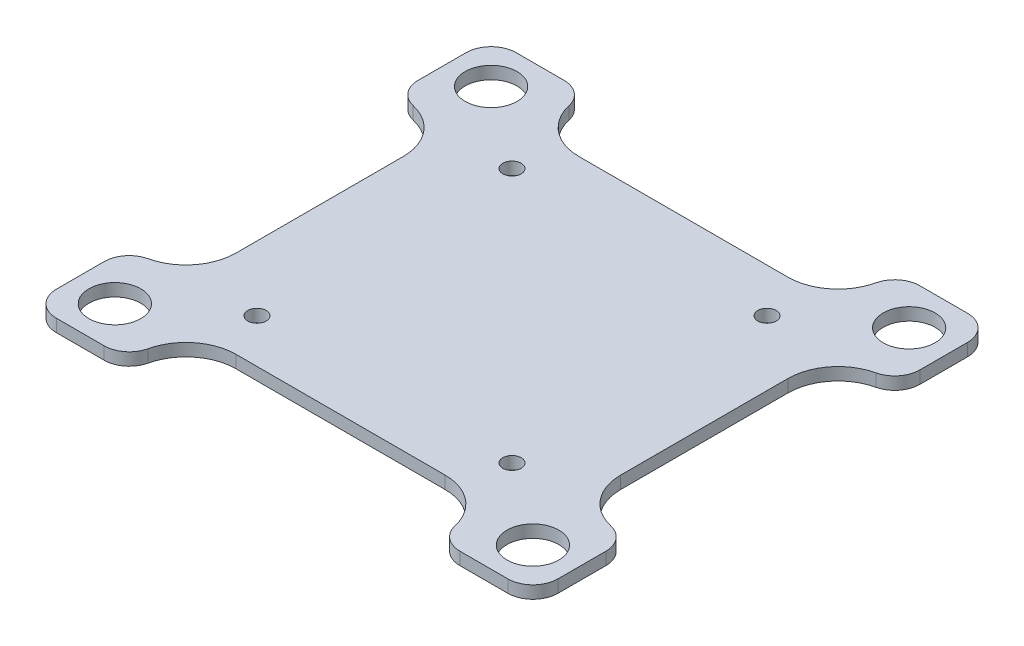
SolidWorks part; units mm, degrees
ref_plane "Front Plane" through (0, 0, 0) normal (0, 0, 1) x (1, 0, 0)
ref_plane "Top Plane" through (0, 0, 0) normal (0, 1, 0) x (1, 0, 0)
ref_plane "Right Plane" through (0, 0, 0) normal (1, 0, 0) x (0, 0, -1)
sketch "Sketch1" plane through (0, 0, 0) normal (0, 1, 0) x (1, 0, 0)
  line L1 (30, 27.5) -> (-30, 27.5)
  line L2 (30, 27.5) -> (30, -27.5)
  line L3 (30, -27.5) -> (-30, -27.5)
  line L4 (-30, 27.5) -> (-30, -27.5)
  line L5 (30, 27.5) -> (-30, -27.5) construction
  line L6 (30, -27.5) -> (-30, 27.5) construction
  point P0 (0, 0)
  dimension "D1" = 60
  dimension "D2" = 55
extrude "Boss-Extrude1" add sketch "Sketch1" along normal blind 1.5
sketch "Sketch2" plane through (0, 1.5, 0) normal (0, 1, 0) x (1, 0, 0)
  line L0 (0, 0) -> (0, -50000) construction
  line L1 (0, 0) -> (-50000, 0) construction
  circle A0 centre (-25, 22.5) radius 3.1
  circle A1 centre (25, 22.5) radius 3.1
  circle A2 centre (-25, -22.5) radius 3.1
  circle A3 centre (25, -22.5) radius 3.1
  dimension "D2" = 6.2
  dimension "D1" = 50
  dimension "D3" = 45
extrude "Cut-Extrude1" cut sketch "Sketch2" against normal through all
fillet "Fillet1" radius 3 4 edges at (30, 0.75, 27.5) (-30, 0.75, 27.5) (30, 0.75, -27.5) (-30, 0.75, -27.5)
sketch "Sketch4" plane through (0, 1.5, 0) normal (0, 1, 0) x (1, 0, 0)
  line L0 (27, 27.5) -> (-27, 27.5) construction
  line L1 (-18.5, 27.5) -> (18.5, 27.5)
  line L2 (-18.5, 27.5) -> (-18.5, 20.5)
  line L3 (-18.5, 20.5) -> (18.5, 20.5)
  line L4 (18.5, 27.5) -> (18.5, 20.5)
  line L5 (0, 0) -> (0, -50000) construction
  line L6 (0, 0) -> (-50000, 0) construction
  line L7 (-30, 24.5) -> (-30, -24.5) construction
  line L8 (-30, 16) -> (-23, 16)
  line L9 (-30, 16) -> (-30, -16)
  line L10 (-30, -16) -> (-23, -16)
  line L11 (-23, 16) -> (-23, -16)
  line L12 (18.5, -27.5) -> (18.5, -20.5)
  line L13 (-18.5, -20.5) -> (18.5, -20.5)
  line L14 (-18.5, -27.5) -> (-18.5, -20.5)
  line L15 (-18.5, -27.5) -> (18.5, -27.5)
  line L16 (23, 16) -> (23, -16)
  line L17 (30, -16) -> (23, -16)
  line L18 (30, 16) -> (30, -16)
  line L19 (30, 16) -> (23, 16)
  dimension "D1" = 37
  dimension "D2" = 7
  dimension "D3" = 32
extrude "Cut-Extrude2" cut sketch "Sketch4" against normal through all
fillet "Fillet2" radius 6 8 edges at (18.5, 0.75, -20.5) (23, 0.75, -16) (23, 0.75, 16) (18.5, 0.75, 20.5) (-18.5, 0.75, 20.5) (-23, 0.75, 16) (-18.5, 0.75, -20.5) (-23, 0.75, -16)
fillet "Fillet3" radius 3 8 edges at (30, 0.75, -16) (18.5, 0.75, -27.5) (30, 0.75, 16) (18.5, 0.75, 27.5) (-18.5, 0.75, 27.5) (-30, 0.75, 16) (-18.5, 0.75, -27.5) (-30, 0.75, -16)
sketch "Sketch5" plane through (0, 1.5, 0) normal (0, 1, 0) x (1, 0, 0)
  line L0 (0, 0) -> (0, -50000) construction
  line L1 (0, 0) -> (-50000, 0) construction
  circle A0 centre (-15.25, 15.25) radius 1.1
  circle A1 centre (15.25, 15.25) radius 1.1
  circle A2 centre (-15.25, -15.25) radius 1.1
  circle A3 centre (15.25, -15.25) radius 1.1
  dimension "D2" = 2.2
  dimension "D1" = 30.5
  dimension "D3" = 30.5
extrude "Cut-Extrude3" cut sketch "Sketch5" against normal through all
